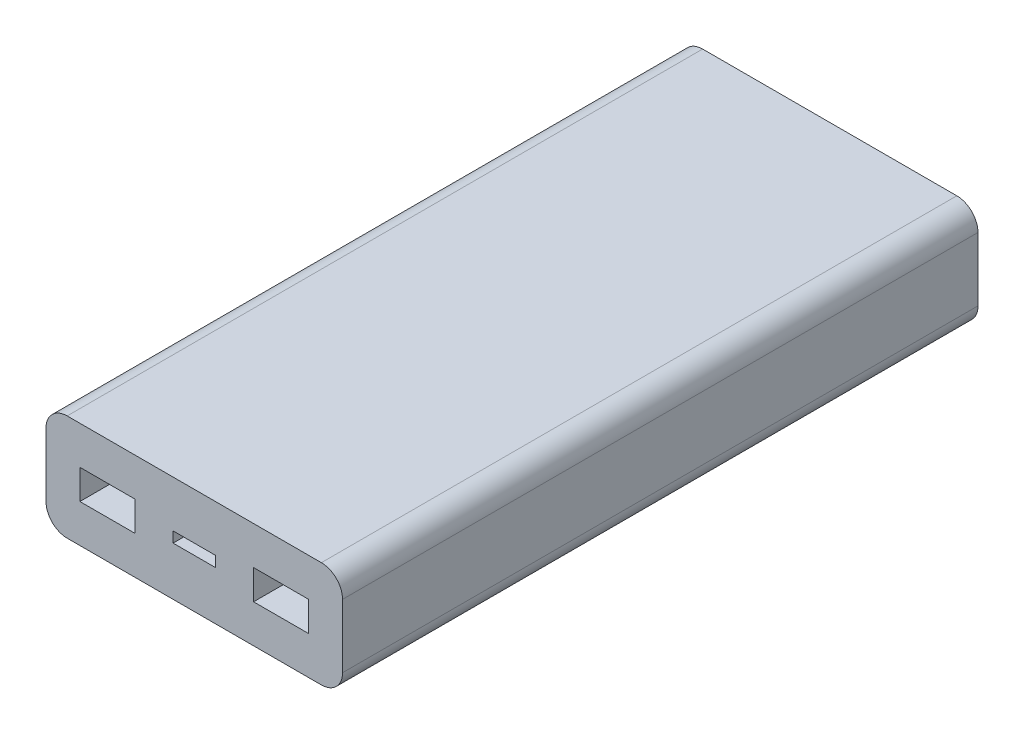
SolidWorks part; units mm, degrees
material "ABS"
ref_plane "Plan de face" through (0, 0, 0) normal (0, 0, 1) x (1, 0, 0)
ref_plane "Plan de dessus" through (0, 0, 0) normal (0, 1, 0) x (1, 0, 0)
ref_plane "Plan de droite" through (0, 0, 0) normal (1, 0, 0) x (0, 0, -1)
sketch "Esquisse1" plane through (0, 0, 0) normal (0, 0, 1) x (1, 0, 0)
  line L1 (0, 0) -> (70, 0)
  line L2 (0, 0) -> (0, 25)
  line L3 (0, 25) -> (70, 25)
  line L4 (70, 0) -> (70, 25)
  dimension "D1" = 70
  dimension "D2" = 25
extrude "Boss.-Extru.1" add sketch "Esquisse1" along normal blind 150
fillet "Congé1" radius 5 4 edges at (0, 0, 75) (70, 0, 75) (70, 25, 75) (0, 25, 75)
sketch "Esquisse2" plane through (0, 0, 150) normal (0, 0, 1) x (1, 0, 0)
  line L0 (0, 20) -> (0, 5) construction
  line L1 (8, 16) -> (21, 16)
  line L2 (8, 16) -> (8, 9)
  line L3 (8, 9) -> (21, 9)
  line L4 (21, 16) -> (21, 9)
  line L5 (49, 16) -> (62, 16)
  line L6 (49, 16) -> (49, 9)
  line L7 (49, 9) -> (62, 9)
  line L8 (62, 16) -> (62, 9)
  line L9 (30, 14) -> (40, 14)
  line L10 (30, 14) -> (30, 11.5)
  line L11 (30, 11.5) -> (40, 11.5)
  line L12 (40, 14) -> (40, 11.5)
  line L13 (70, 5) -> (70, 20) construction
  line L14 (65, 25) -> (5, 25) construction
  line L15 (5, 0) -> (65, 0) construction
  point P14 (0, 12.5)
  dimension "D1" = 8
  dimension "D2" = 8
  dimension "D3" = 9
  dimension "D4" = 9
  dimension "D5" = 9
  dimension "D6" = 9
  dimension "D7" = 13
  dimension "D8" = 13
  dimension "D9" = 11
  dimension "D10" = 2.5
  dimension "D11" = 30
  dimension "D12" = 30
extrude "Enlèv. mat.-Extru.1" cut sketch "Esquisse2" against normal blind 11.5
